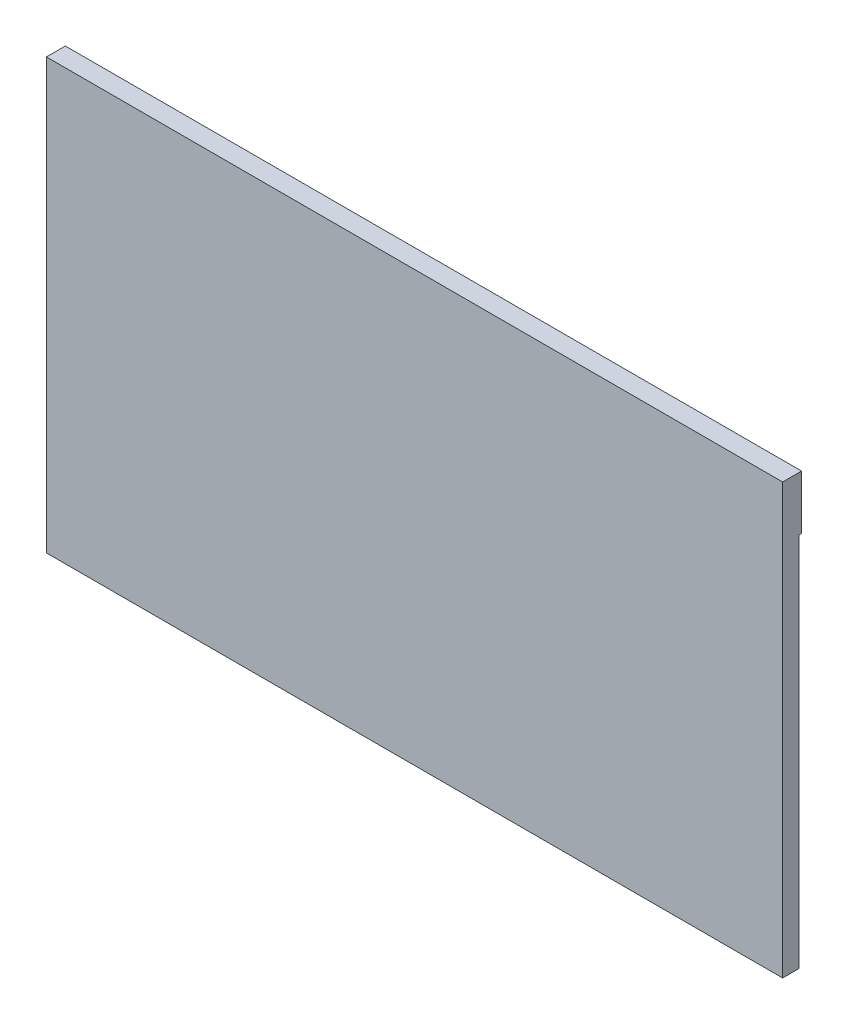
SolidWorks part; units mm, degrees
ref_plane "Plan de face" through (0, 0, 0) normal (0, 0, 1) x (1, 0, 0)
ref_plane "Plan de dessus" through (0, 0, 0) normal (0, 1, 0) x (1, 0, 0)
ref_plane "Plan de droite" through (0, 0, 0) normal (1, 0, 0) x (0, 0, -1)
sketch "Esquisse1" plane through (0, 0, 0) normal (0, 0, 1) x (1, 0, 0)
  line L1 (-272.5, 159) -> (272.5, 159)
  line L2 (-272.5, 159) -> (-272.5, -159)
  line L3 (-272.5, -159) -> (272.5, -159)
  line L4 (272.5, 159) -> (272.5, -159)
  line L5 (-272.5, 159) -> (272.5, -159) construction
  line L6 (-272.5, -159) -> (272.5, 159) construction
  point P0 (0, 0)
  dimension "D1" = 545
  dimension "D2" = 318
extrude "Boss.-Extru.1" add sketch "Esquisse1" along normal blind 12
sketch "Esquisse2" plane through (0, 0, 0) normal (0, 0, -1) x (-1, 0, 0)
  line L0 (272.5, 159) -> (272.5, -159) construction
  line L1 (-272.5, 159) -> (272.5, 159)
  line L2 (-272.5, 159) -> (-272.5, 119)
  line L3 (-272.5, 119) -> (272.5, 119)
  line L4 (272.5, 159) -> (272.5, 119)
  dimension "D1" = 40
extrude "Boss.-Extru.2" add sketch "Esquisse2" along normal blind 2
sketch "Esquisse3" plane through (0, 0, 0) normal (0, 0, -1) x (-1, 0, 0)
  line L0 (-272.5, -159) -> (-272.5, 119) construction
  line L1 (-197.5, 139) -> (-147.5, 139)
  line L2 (-197.5, 139) -> (-197.5, 109)
  line L3 (-197.5, 109) -> (-147.5, 109)
  line L4 (-147.5, 139) -> (-147.5, 109)
  line L5 (272.5, 159) -> (-272.5, 159) construction
  dimension "D1" = 50
  dimension "D2" = 125
  dimension "D3" = 50
  dimension "D4" = 30
extrude "Boss.-Extru.3" add sketch "Esquisse3" along normal blind 4
